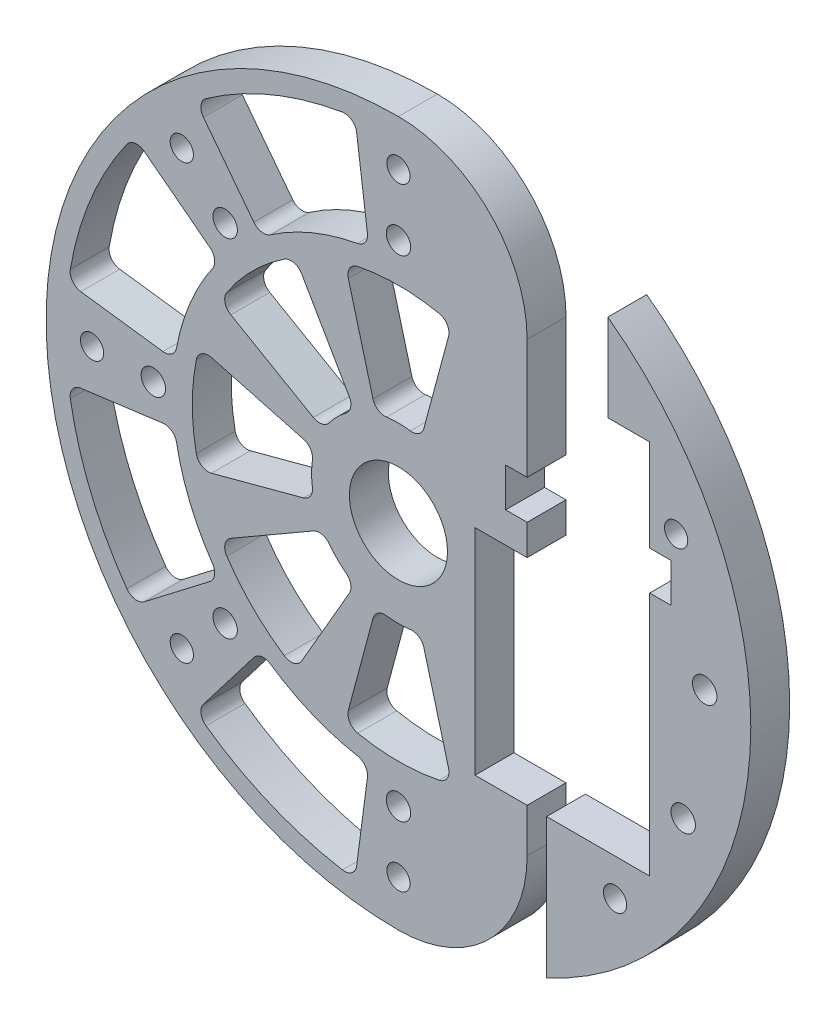
SolidWorks part; units mm, degrees
material "Balsa"
ref_plane "Front Plane" through (0, 0, 0) normal (0, 0, 1) x (1, 0, 0)
ref_plane "Top Plane" through (0, 0, 0) normal (0, 1, 0) x (1, 0, 0)
ref_plane "Right Plane" through (0, 0, 0) normal (1, 0, 0) x (0, 0, -1)
sketch "Sketch1" plane through (0, 0, 0) normal (0, 0, 1) x (1, 0, 0)
  line L0 (45.3154, 21.1309) -> (0, 0) construction
  line L1 (0, 0) -> (35.3553, -35.3553) construction
  line L2 (49.9788, 1.4542) -> (0, 0) construction
  line L3 (0, 0) -> (46.4674, -18.4603) construction
  circle A0 centre (45.3154, 21.1309) radius 1.8986
  circle A1 centre (46.4674, -18.4603) radius 1.9939
  circle A2 centre (0, 0) radius 57.5
  circle A3 centre (0, 0) radius 8
  circle A4 centre (49.9788, 1.4542) radius 1.9939
  circle A5 centre (0, 0) radius 40 construction
  circle A6 centre (0, 0) radius 50 construction
  circle A29 centre (0, -40) radius 1.9939
  circle A30 centre (0, -50) radius 1.8986
  circle A37 centre (-28.2843, -28.2843) radius 1.9939
  circle A38 centre (-35.3553, -35.3553) radius 1.8986
  circle A39 centre (-40, 0) radius 1.9939
  circle A40 centre (-50, 0) radius 1.8986
  circle A41 centre (-28.2843, 28.2843) radius 1.9939
  circle A42 centre (-35.3553, 35.3553) radius 1.8986
  circle A43 centre (0, 40) radius 1.9939
  circle A44 centre (0, 50) radius 1.8986
  circle A45 centre (28.2843, 28.2843) radius 1.9939 construction
  circle A46 centre (35.3553, 35.3553) radius 1.8986 construction
  circle A47 centre (40, 0) radius 1.9939 construction
  circle A48 centre (50, 0) radius 1.8986 construction
  circle A49 centre (28.2843, -28.2843) radius 1.9939 construction
  circle A50 centre (35.3553, -35.3553) radius 1.8986
  dimension "D1" = 115
  dimension "D4" = 3.7973
  dimension "D6" = 100
  dimension "D7" = 80
  dimension "D8" = 3.9878
  dimension "D9" = 3.9878
  dimension "D10" = 23.333
  dimension "D15" = 3.7973
  dimension "D16" = 3.9878
  dimension "D5" = 70
  dimension "D3" = 16
  dimension "D11" = 23.333
  dimension "D21" = 8
extrude "Boss-Extrude1" add sketch "Sketch1" along normal blind 6.35
sketch "Sketch2" plane through (0, 0, 0) normal (0, 0, 1) x (1, 0, 0)
  line L0 (12.5, -29.35) -> (41, -29.35)
  line L1 (41, -29.35) -> (41, 10.65)
  line L2 (41, 10.65) -> (44.5, 10.65)
  line L3 (44.5, 10.65) -> (44.5, 17)
  line L4 (44.5, 17) -> (41, 17)
  line L5 (41, 17) -> (41, 32)
  line L6 (41, 32) -> (21, 32)
  line L7 (21, 32) -> (21, 17)
  line L8 (21, 17) -> (17.5, 17)
  line L9 (17.5, 17) -> (17.5, 10.65)
  line L10 (17.5, 10.65) -> (21, 10.65)
  line L11 (21, 10.65) -> (21, 5.65)
  line L12 (21, 5.65) -> (12.5, 5.65)
  line L13 (12.5, 5.65) -> (12.5, -29.35)
  dimension "D2" = 20
  dimension "D3" = 3.5
  dimension "D4" = 3.5
  dimension "D5" = 15
  dimension "D6" = 21
  dimension "D7" = 6.35
  dimension "D8" = 5
  dimension "D9" = 40
  dimension "D10" = 8.5
  dimension "D11" = 32
extrude "Cut-Extrude1" cut sketch "Sketch2" along normal through all
sketch "Sketch3" plane through (0, 0, 6.35) normal (0, 0, 1) x (1, 0, 0)
  line L0 (41, 32) -> (21, 32) construction
  line L1 (27.825, -8) -> (34.175, -8)
  line L2 (27.825, -8) -> (27.825, 72)
  line L3 (27.825, 72) -> (34.175, 72)
  line L4 (34.175, -8) -> (34.175, 72)
  line L5 (27.825, -8) -> (34.175, 72) construction
  line L6 (27.825, 72) -> (34.175, -8) construction
  point P0 (31, 32)
  dimension "D1" = 6.35
  dimension "D2" = 80
extrude "Cut-Extrude3" cut sketch "Sketch3" against normal through all
sketch "Sketch4" plane through (0, 0, 6.35) normal (0, 0, 1) x (1, 0, 0)
  line L0 (21, -36.5) -> (21, -16.443)
  line L1 (27.825, 32) -> (34.175, 32) construction
  line L2 (21, -16.443) -> (24.175, -16.4703)
  line L3 (24.175, -16.4703) -> (24.175, -57.5)
  line L4 (0, -57.5) -> (24.175, -57.5)
  line L5 (0, 0) -> (98.5911, 0) construction
  line L6 (0, 57.5) -> (24.175, 57.5)
  line L7 (24.175, 16.4703) -> (24.175, 57.5)
  line L8 (21, 16.443) -> (24.175, 16.4703)
  line L9 (21, 36.5) -> (21, 16.443)
  arc A0 (0, -57.5) -> (21, -36.5) centre (0, -36.5) ccw
  arc A1 (0, 57.5) -> (21, 36.5) centre (0, 36.5) cw
  arc A2 (27.825, 50.3192) -> (34.175, 46.242) centre (0, 0) ccw construction
  point P13 (31, 32)
  point P14 (22.5875, -16.4566)
  dimension "D3" = 3.175
  dimension "D4" = 8.4125
extrude "Cut-Extrude4" cut sketch "Sketch4" against normal through all
sketch "Sketch5" plane through (0, 0, 6.35) normal (0, 0, 1) x (1, 0, 0)
  line L3 (24.175, 52.1711) -> (24.175, 32)
  line L4 (24.175, 32) -> (27.825, 32)
  line L5 (27.825, 32) -> (27.825, 50.3192)
  line L6 (24.175, 52.1711) -> (24.175, 32)
  line L7 (24.175, 32) -> (27.825, 32)
  line L8 (27.825, 32) -> (27.825, 50.3192)
  arc A1 (27.825, 50.3192) -> (24.175, 52.1711) centre (0, 0) ccw
  arc A2 (27.825, 50.3192) -> (24.175, 52.1711) centre (0, 0) ccw
  dimension "D1" = 0
extrude "Cut-Extrude5" cut sketch "Sketch5" against normal through all
sketch "Sketch6" plane through (0, 0, 6.35) normal (0, 0, 1) x (1, 0, 0)
  line L0 (-13.692, 3.6688) -> (-32.5034, 8.7093)
  line L1 (-13.692, -3.6688) -> (-32.5034, -8.7093)
  line L2 (0, 0) -> (-74.5627, 0) construction
  arc A0 (-13.692, -3.6688) -> (-13.692, 3.6688) centre (0, 0) cw
  arc A1 (-32.5034, -8.7093) -> (-32.5034, 8.7093) centre (0, 0) cw
  circle A2 centre (0, 0) radius 8 construction
  circle A3 centre (-40, 0) radius 1.9939 construction
  point P8 (-33.65, 0)
  dimension "D1" = 6.175
  dimension "D2" = 6.35
  dimension "D3" = 30
extrude "Cut-Extrude6" cut sketch "Sketch6" against normal through all
fillet "Fillet1" radius 2 4 edges at (-32.5034, -8.7093, 3.175) (-13.692, -3.6688, 3.175) (-13.692, 3.6688, 3.175) (-32.5034, 8.7093, 3.175)
pattern_circular "CirPattern1" count 8 over 360 about axis through (0, 0, 0) along (0, 0, 1) skipping 3, 4, 5 of "Fillet1", "Cut-Extrude6"
sketch "Sketch7" plane through (0, 0, 6.35) normal (0, 0, 1) x (1, 0, 0)
  line L0 (-43.0989, 33.071) -> (-29.2152, 22.4176)
  line L1 (-36.51, 4.8066) -> (-53.8602, 7.0908)
  line L2 (0, 0) -> (-63.1273, 26.1482) construction
  line L3 (0, 0) -> (-71.1611, 0) construction
  arc A0 (-36.51, 4.8066) -> (-29.2152, 22.4176) centre (0, 0) cw
  arc A1 (-43.0989, 33.071) -> (-53.8602, 7.0908) centre (0, 0) ccw
  circle A2 centre (-28.2843, 28.2843) radius 1.9939 construction
  circle A3 centre (-35.3553, 35.3553) radius 1.8987 construction
  circle A4 centre (-28.2843, 28.2843) radius 1.9939 construction
  circle A5 centre (-35.3553, 35.3553) radius 1.8986 construction
  arc A6 (-32.9888, 6.6379) -> (-32.9888, -6.6379) centre (0, 0) ccw construction
  arc A7 (0, 57.5) -> (0, -57.5) centre (0, 0) ccw construction
  point P12 (-34.0219, 14.0923)
  dimension "D3" = 3.175
  dimension "D4" = 3.175
  dimension "D1" = 22.5
  dimension "D2" = 30
extrude "Cut-Extrude7" cut sketch "Sketch7" against normal blind 10
fillet "Fillet2" radius 2 4 edges at (-53.8602, 7.0908, 3.175) (-36.51, 4.8066, 3.175) (-29.2152, 22.4176, 3.175) (-43.0989, 33.071, 3.175)
pattern_circular "CirPattern2" count 8 over 360 about axis through (0, 0, 0) along (0, 0, 1) skipping 2, 3, 4, 5 of "Cut-Extrude7", "Fillet2"
